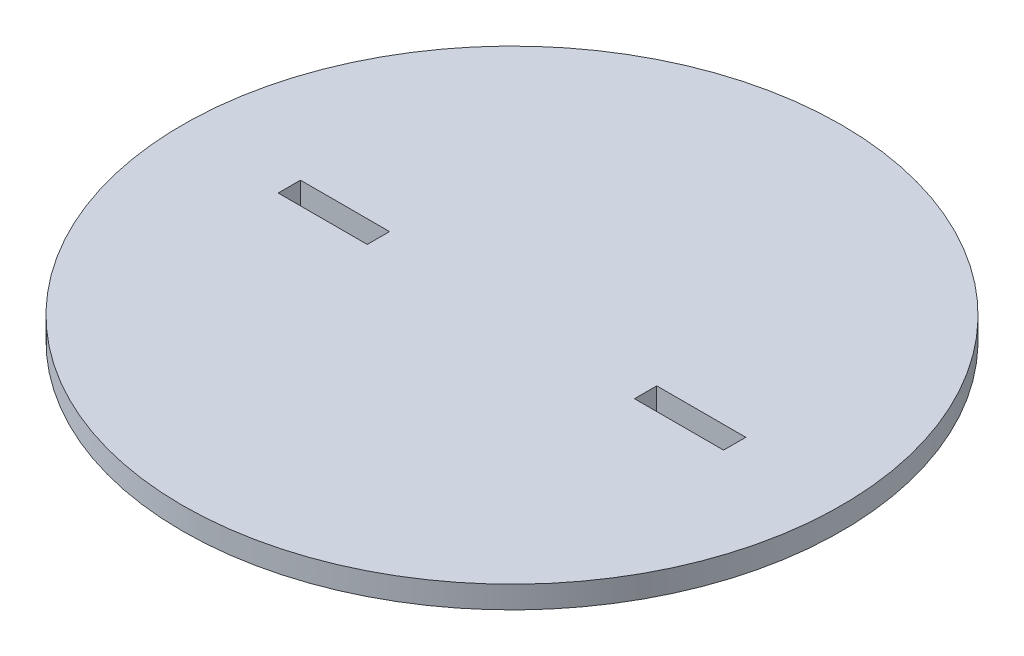
SolidWorks part; units mm, degrees
material "E-Glass Fiber"
ref_plane "Front Plane" through (0, 0, 0) normal (0, 0, 1) x (1, 0, 0)
ref_plane "Top Plane" through (0, 0, 0) normal (0, 1, 0) x (1, 0, 0)
ref_plane "Right Plane" through (0, 0, 0) normal (1, 0, 0) x (0, 0, -1)
sketch "Sketch1" plane through (0, 0, 0) normal (0, 1, 0) x (1, 0, 0)
  circle A0 centre (0, 0) radius 23.495
  dimension "D1" = 46.99
extrude "Boss-Extrude1" add sketch "Sketch1" along normal blind 1.5875
sketch "Sketch2" plane through (0, 1.5875, 0) normal (0, 1, 0) x (1, 0, 0)
  line L0 (-9.525, 0) -> (9.525, 0) construction
  line L1 (-9.525, -0.7937) -> (-15.875, -0.7937)
  line L2 (-9.525, -0.7937) -> (-9.525, 0.7937)
  line L3 (-9.525, 0.7937) -> (-15.875, 0.7938)
  line L4 (-15.875, -0.7937) -> (-15.875, 0.7938)
  line L5 (9.525, -0.7937) -> (15.875, -0.7938)
  line L6 (9.525, -0.7937) -> (9.525, 0.7937)
  line L7 (9.525, 0.7937) -> (15.875, 0.7938)
  line L8 (15.875, -0.7938) -> (15.875, 0.7938)
  dimension "D1" = 1.5875
  dimension "D2" = 6.35
  dimension "D3" = 19.05
extrude "Cut-Extrude1" cut sketch "Sketch2" against normal through all
